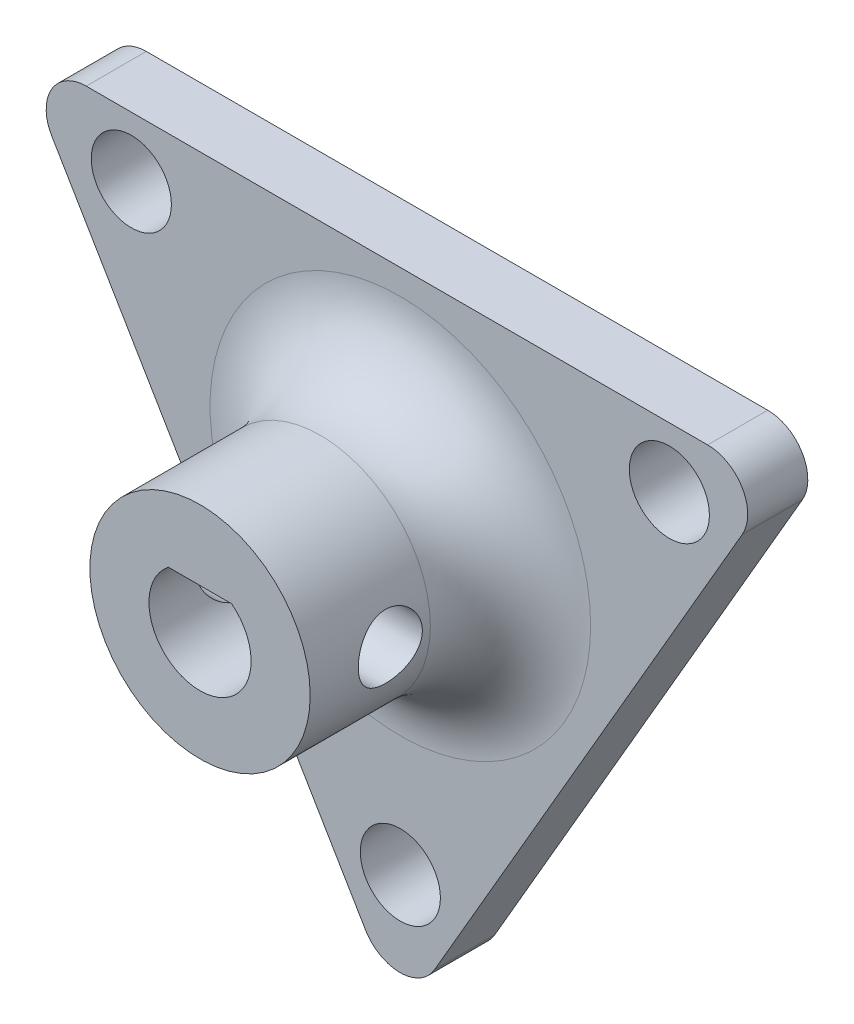
SolidWorks part; units mm, degrees
ref_plane "Front Plane" through (0, 0, 0) normal (0, 0, 1) x (1, 0, 0)
ref_plane "Top Plane" through (0, 0, 0) normal (0, 1, 0) x (1, 0, 0)
ref_plane "Right Plane" through (0, 0, 0) normal (1, 0, 0) x (0, 0, -1)
sketch "Sketch1" plane through (0, 0, 0) normal (0, 0, 1) x (1, 0, 0)
  line L0 (-13.4298, 11.6306) -> (13.4298, 11.6306) construction
  line L1 (0, 11.6306) -> (0, -11.6306) construction
  line L5 (-19.1863, 14.6306) -> (18.8137, 14.6306)
  line L6 (18.8137, 14.6306) -> (0, -17.8211)
  line L7 (0, -17.8211) -> (-19.1863, 14.6306)
  circle A0 centre (-13.4298, 11.6306) radius 2
  circle A1 centre (13.4298, 11.6306) radius 2
  circle A2 centre (0, -11.6306) radius 2
  point P7 (0, 11.6306)
  point P19 (0, 0)
  dimension "D1" = 26.8596
  dimension "D2" = 26.8596
  dimension "D3" = 26.8596
  dimension "D4" = 3
  dimension "D5" = 38
extrude "Boss-Extrude1" add sketch "Sketch1" along normal blind 3
sketch "Sketch2" plane through (0, 0, 3) normal (0, 0, 1) x (1, 0, 0)
  line L0 (-11.4298, 11.6306) -> (11.4298, 11.6306) construction
  circle A1 centre (0, 3.8806) radius 5.5
  circle A2 centre (-13.4298, 11.6306) radius 2 construction
  circle A3 centre (13.4298, 11.6306) radius 2 construction
  dimension "D1" = 11
  dimension "D2" = 7.75
extrude "Boss-Extrude2" add sketch "Sketch2" along normal blind 10
sketch "Sketch3" plane through (0, 0, 13) normal (0, 0, 1) x (1, 0, 0)
  line L1 (-5.5, 3.8806) -> (5.5, 3.8806) construction
  line L2 (-1.5819, 5.8806) -> (1.5819, 5.8806)
  circle A3 centre (0, 3.8806) radius 5.5 construction
  circle A4 centre (0, 3.8806) radius 5.5 construction
  arc A6 (-1.5819, 5.8806) -> (1.5819, 5.8806) centre (0, 3.8806) ccw
  dimension "D1" = 2.55
  dimension "D2" = 2
extrude "Cut-Extrude1" cut sketch "Sketch3" against normal through all both and the other way through all
fillet "Fillet1" radius 2 3 edges at (0, -17.8211, 1.5) (18.8137, 14.6306, 1.5) (-19.1863, 14.6306, 1.5)
fillet "Fillet2" radius 4 1 edges at (5.5, 3.8806, 3)
sketch "Sketch4" plane through (0, 0, 0) normal (1, 0, 0) x (0, 0, -1)
  line L0 (-13, 3.8806) -> (-5, 3.8806) construction
  line L1 (-13, 9.3806) -> (-13, -1.6194) construction
  line L3 (-7, 9.3806) -> (-3, 9.3806) construction
  line L4 (-3, 13.3806) -> (-3, -5.6194) construction
  circle A0 centre (-9, 3.8806) radius 1.6
  point P12 (-5, 9.3806)
  dimension "D1" = 3.2
extrude "Cut-Extrude2" cut sketch "Sketch4" against normal through all both and the other way through all
